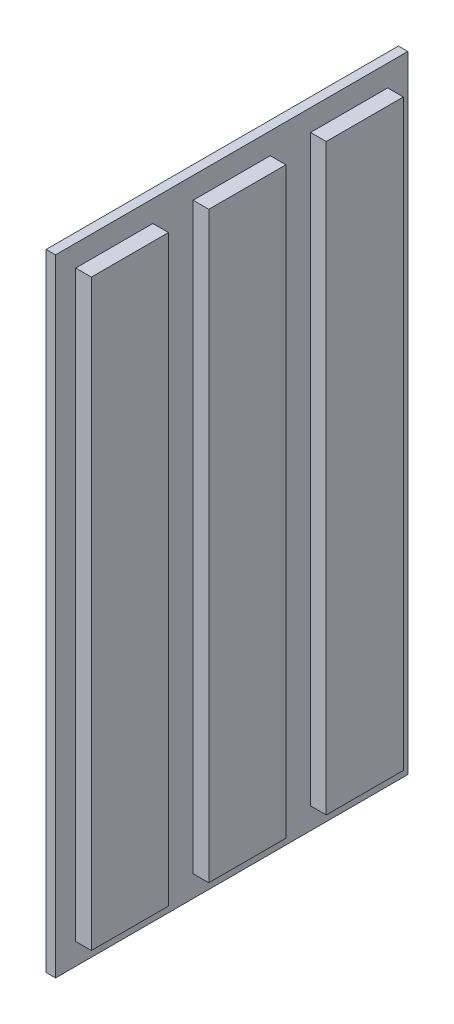
SolidWorks part; units mm, degrees
ref_plane "Front Plane" through (0, 0, 0) normal (1, 0, 0) x (0, 1, 0)
ref_plane "Top Plane" through (0, 0, 0) normal (0, 0, 1) x (0, 1, 0)
ref_plane "Right Plane" through (0, 0, 0) normal (0, 1, 0) x (-1, 0, 0)
sketch "Sketch1" plane through (0, 0, 0) normal (1, 0, 0) x (0, 1, 0)
  line L1 (40, -22.5) -> (-40, -22.5)
  line L2 (40, -22.5) -> (40, 22.5)
  line L3 (40, 22.5) -> (-40, 22.5)
  line L4 (-40, -22.5) -> (-40, 22.5)
  line L5 (40, -22.5) -> (-40, 22.5) construction
  line L6 (40, 22.5) -> (-40, -22.5) construction
  point P0 (0, 0)
  dimension "D1" = 80
  dimension "D2" = 45
extrude "Boss-Extrude1" add sketch "Sketch1" against normal blind 1.2
sketch "Sketch2" plane through (0, 0, 0) normal (1, 0, 0) x (0, 1, 0)
  line L0 (0, -1.76) -> (0, 1.76) construction
  line L1 (37.25, 10.075) -> (-37.25, 10.075)
  line L2 (37.25, 10.075) -> (37.25, 19.925)
  line L3 (37.25, 19.925) -> (-37.25, 19.925)
  line L4 (-37.25, 10.075) -> (-37.25, 19.925)
  line L5 (37.25, 10.075) -> (-37.25, 19.925) construction
  line L6 (37.25, 19.925) -> (-37.25, 10.075) construction
  line L7 (40, 22.5) -> (-40, 22.5) construction
  point P0 (0, 15)
  dimension "D1" = 74.5
  dimension "D2" = 9.85
  dimension "D3" = 7.5
extrude "Boss-Extrude2" add sketch "Sketch2" along normal blind 2
ref_plane "Plane1" through (0, 0, 15) normal (0, 0, 1) x (0, -1, 0)
pattern_linear "LPattern1" count 3 spacing 15 along (0, 0, -1) of "Boss-Extrude2"
sketch "Sketch3" plane through (-1.2, 0, 0) normal (-1, 0, 0) x (0, -1, 0)
  line L0 (-40, 4.925) -> (40, 4.925) construction
  line L3 (-37.25, 4.925) -> (37.25, 4.925) construction
  text T0 "<b>92223061_A</b>" font "Century Gothic" height 3.5
extrude "Cut-Extrude1" cut sketch "Sketch3" against normal blind 0.6
